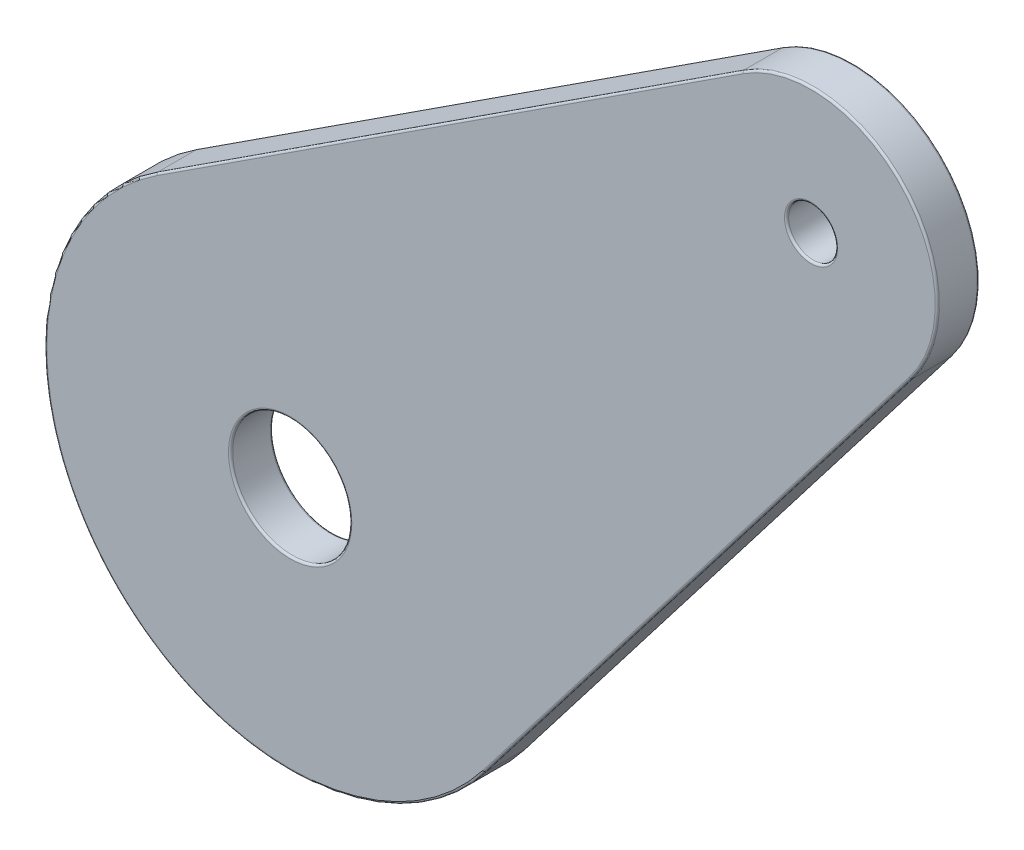
SolidWorks part; units mm, degrees
material "Plain Carbon Steel"
ref_plane "Front Plane" through (0, 0, 0) normal (0, 0, 1) x (1, 0, 0)
ref_plane "Top Plane" through (0, 0, 0) normal (0, 1, 0) x (1, 0, 0)
ref_plane "Right Plane" through (0, 0, 0) normal (1, 0, 0) x (0, 0, -1)
sketch "Sketch1" plane through (0, 0, 0) normal (0, 0, 1) x (1, 0, 0)
  line L0 (-20.22, 57.58) -> (16.9307, 91.8876) construction
  line L1 (-20.22, 57.58) -> (16.9307, 91.8876) construction
  line L2 (-6.3553, 46.902) -> (24.0611, 86.396)
  line L5 (-29.7627, 72.2493) -> (12.023, 99.4318)
  circle A2 centre (-20.22, 57.58) radius 9 construction
  circle A3 centre (16.9307, 91.8876) radius 9 construction
  circle A4 centre (-20.22, 57.58) radius 17.5 construction
  circle A5 centre (-20.22, 57.58) radius 17.5 construction
  arc A6 (-29.7627, 72.2493) -> (-6.3553, 46.902) centre (-20.22, 57.58) ccw
  arc A7 (12.023, 99.4318) -> (24.0611, 86.396) centre (16.9307, 91.8876) cw
  circle A8 centre (-20.22, 57.58) radius 4.25
  circle A9 centre (16.9307, 91.8876) radius 1.75
  dimension "D2" = 18
  dimension "D1" = 8.5
  dimension "D3" = 3.5
extrude "Boss-Extrude1" add sketch "Sketch1" along normal blind 3
fillet "Fillet2" radius 0.15 12 edges at (8.8529, 66.649, 3) (-33.0765, 45.7074, 3) (-8.8698, 85.8405, 3) (23.5426, 97.9935, 3) (-15.97, 57.58, 3) (18.6807, 91.8876, 3) (-8.8698, 85.8405, 0) (-33.0765, 45.7074, 0) (8.8529, 66.649, 0) (23.5426, 97.9935, 0) (-15.97, 57.58, 0) (18.6807, 91.8876, 0)
